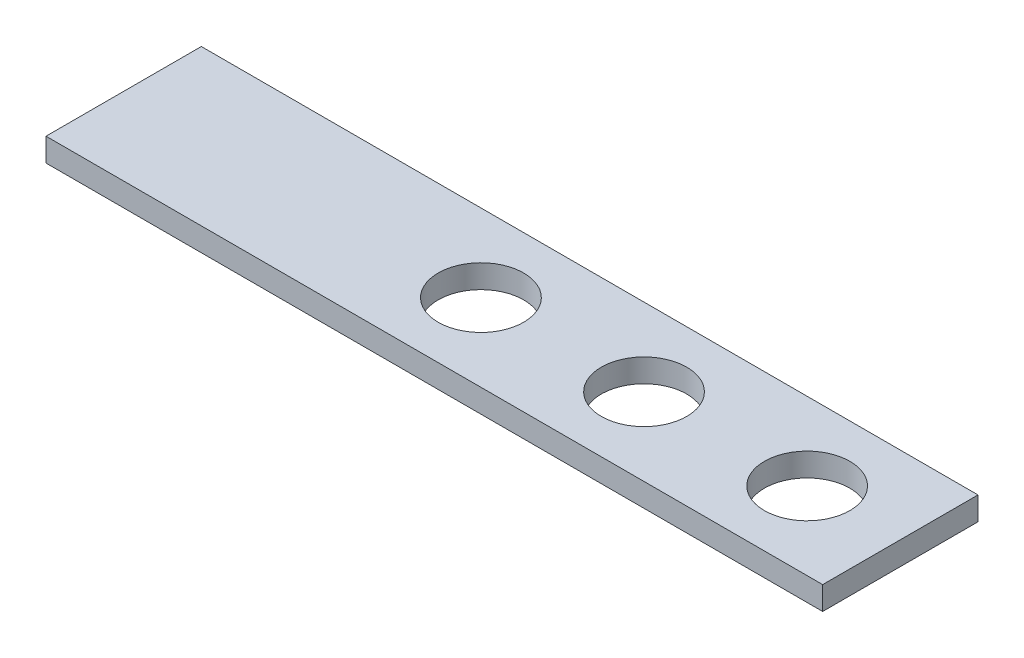
SolidWorks part; units mm, degrees
material "Acrylic (Medium-high impact)"
ref_plane "Front Plane" through (0, 0, 0) normal (0, 0, 1) x (1, 0, 0)
ref_plane "Top Plane" through (0, 0, 0) normal (0, 1, 0) x (1, 0, 0)
ref_plane "Right Plane" through (0, 0, 0) normal (1, 0, 0) x (0, 0, -1)
sketch "Sketch1" plane through (0, 0, 0) normal (0, 1, 0) x (1, 0, 0)
  line L0 (0, 0) -> (0, 20)
  line L3 (0, 20) -> (100, 20)
  line L4 (100, 20) -> (100, 0)
  line L5 (100, 0) -> (0, 0)
  circle A0 centre (46, 10) radius 5.5
  circle A1 centre (67, 10) radius 5.5
  circle A2 centre (88, 10) radius 5.5
  dimension "D6" = 11
  dimension "D7" = 11
  dimension "D8" = 11
  dimension "D1" = 20
  dimension "D2" = 100
  dimension "D9" = 21
  dimension "D10" = 21
  dimension "D3" = 10
  dimension "D4" = 12
extrude "Boss-Extrude1" add sketch "Sketch1" along normal blind 3
equation "\"D7@Sketch1\"=\"D6@Sketch1\""
equation "\"D8@Sketch1\"=\"D6@Sketch1\""
